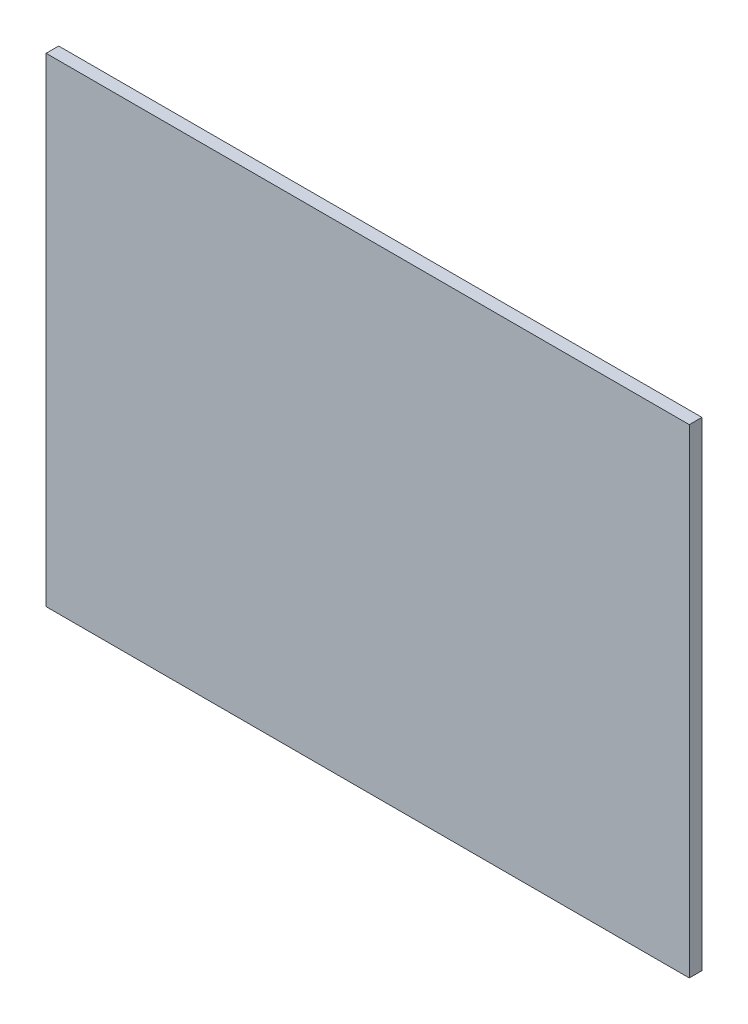
SolidWorks part; units mm, degrees
ref_plane "Front Plane" through (0, 0, 0) normal (0, 0, 1) x (1, 0, 0)
ref_plane "Top Plane" through (0, 0, 0) normal (0, 1, 0) x (1, 0, 0)
ref_plane "Right Plane" through (0, 0, 0) normal (1, 0, 0) x (0, 0, -1)
sketch "Sketch2" plane through (0, 0, 0) normal (0, 0, 1) x (1, 0, 0)
  line L1 (0, 0) -> (510, 0)
  line L2 (0, 0) -> (0, 380)
  line L3 (0, 380) -> (510, 380)
  line L4 (510, 0) -> (510, 380)
  dimension "D1" = 510
  dimension "D2" = 380
extrude "Boss-Extrude1" add sketch "Sketch2" along normal blind 10
